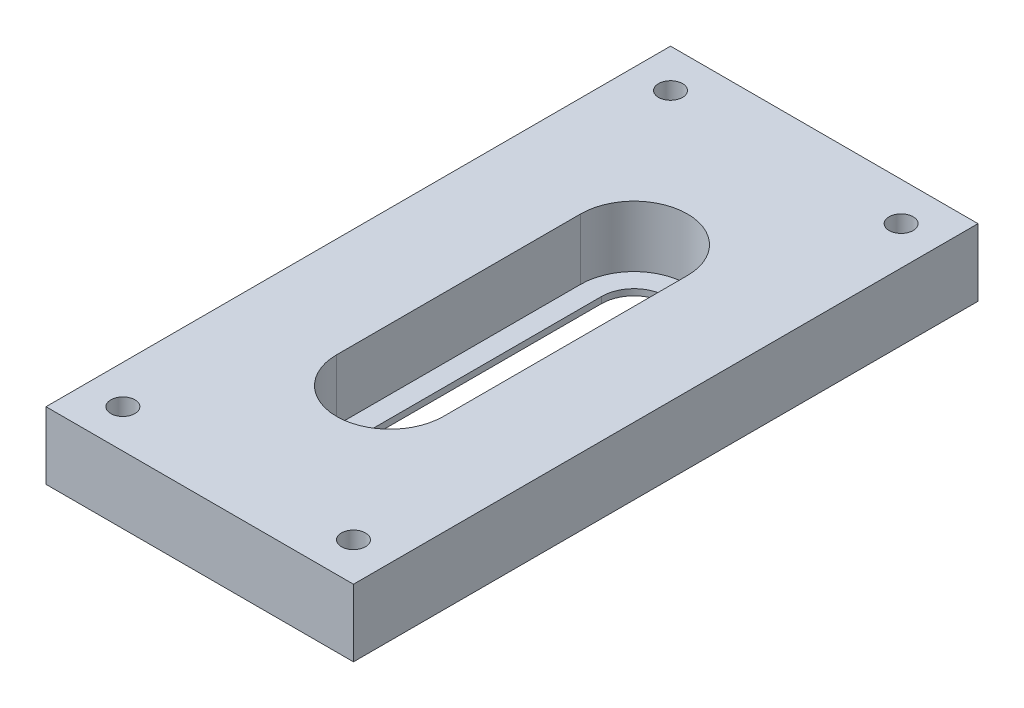
SolidWorks part; units mm, degrees
ref_plane "Front Plane" through (0, 0, 0) normal (0, 0, 1) x (1, 0, 0)
ref_plane "Top Plane" through (0, 0, 0) normal (0, 1, 0) x (1, 0, 0)
ref_plane "Right Plane" through (0, 0, 0) normal (1, 0, 0) x (0, 0, -1)
sketch "Sketch1" plane through (0, 27.9281, 0) normal (0, -1, 0) x (1, 0, 0)
  line L1 (38.9644, 11.5916) -> (6.9644, 11.5916)
  line L2 (38.9644, 11.5916) -> (38.9644, 76.5916)
  line L3 (38.9644, 76.5916) -> (6.9644, 76.5916)
  line L4 (6.9644, 11.5916) -> (6.9644, 76.5916)
extrude "Boss-Extrude1" add sketch "Sketch1" along normal blind 7
hole_wizard "Tap Drill for M3x0.5 Tap1" positions "Sketch2" profile "Sketch3" hole size "M3x0.5" standard "ANSI Metric" end condition through all
sketch "Sketch2" plane through (0, 27.9281, 0) normal (0, 1, 0) x (1, 0, 0)
  point P0 (10.9644, -15.5916)
  point P3 (34.9644, -15.5916)
  point P6 (34.9644, -72.5916)
  point P9 (10.9644, -72.5916)
sketch "Sketch3" plane through (10.9644, 27.9281, 15.5916) normal (1, 0, 0) x (0, 0, 1)
  line L0 (0, 0) -> (0, 7)
  line L1 (0, 7) -> (1.25, 7)
  line L2 (1.25, 7) -> (1.25, 0)
  line L5 (1.25, 0) -> (0, 0)
  line L11 (0, -6.35) -> (0, 107.95) construction
  dimension "Thru Hole Dia." = 2.5
  dimension "Thru Hole Depth" = 7
hole_wizard "CBORE for 1/4 Socket Head Cap Screw1" positions "Sketch4" profile "Sketch5" counterbore size "1/4" standard "ANSI Inch" end condition through all
sketch "Sketch4" plane through (0, 27.9281, 0) normal (0, 1, 0) x (1, 0, 0)
  point P0 (22.9644, -31.3916)
  point P2 (22.9644, -56.7916)
sketch "Sketch5" plane through (22.9644, 27.9281, 31.3916) normal (1, 0, 0) x (0, 0, 1)
  line L0 (0, 0) -> (0, 7)
  line L1 (0, 7) -> (3.3782, 7)
  line L3 (3.3782, 7) -> (3.3782, 6.35)
  line L4 (3.3782, 6.35) -> (5.5562, 6.35)
  line L5 (5.5562, 6.35) -> (5.5563, 0)
  line L7 (5.5563, 0) -> (0, 0)
  line L11 (0, -6.35) -> (0, 107.95) construction
  dimension "Thru Hole Dia." = 6.7564
  dimension "Thru Hole Depth" = 7
  dimension "C'Bore Dia." = 11.1125
  dimension "C'Bore Depth" = 6.35
sketch "Sketch6" plane through (0, 27.9281, 0) normal (0, 1, 0) x (1, 0, 0)
  line L1 (17.4081, -31.3916) -> (28.5206, -31.3916)
  line L2 (17.4081, -31.3916) -> (17.4081, -56.7916)
  line L3 (17.4081, -56.7916) -> (28.5206, -56.7916)
  line L4 (28.5206, -31.3916) -> (28.5206, -56.7916)
  circle A0 centre (22.9644, -31.3916) radius 5.5562 construction
  circle A1 centre (22.9644, -56.7916) radius 5.5562 construction
extrude "Cut-Extrude1" cut sketch "Sketch6" against normal up to surface (6.35 mm away) up to face at (22.9644, 21.5781, 34.7698)
sketch "Sketch7" plane through (0, 21.5781, 0) normal (0, 1, 0) x (1, 0, 0)
  line L1 (19.5862, -31.3916) -> (26.3426, -31.3916)
  line L2 (19.5862, -31.3916) -> (19.5862, -56.7916)
  line L3 (19.5862, -56.7916) -> (26.3426, -56.7916)
  line L4 (26.3426, -31.3916) -> (26.3426, -56.7916)
  circle A0 centre (22.9644, -31.3916) radius 3.3782 construction
  circle A1 centre (22.9644, -56.7916) radius 3.3782 construction
extrude "Cut-Extrude2" cut sketch "Sketch7" against normal through all
